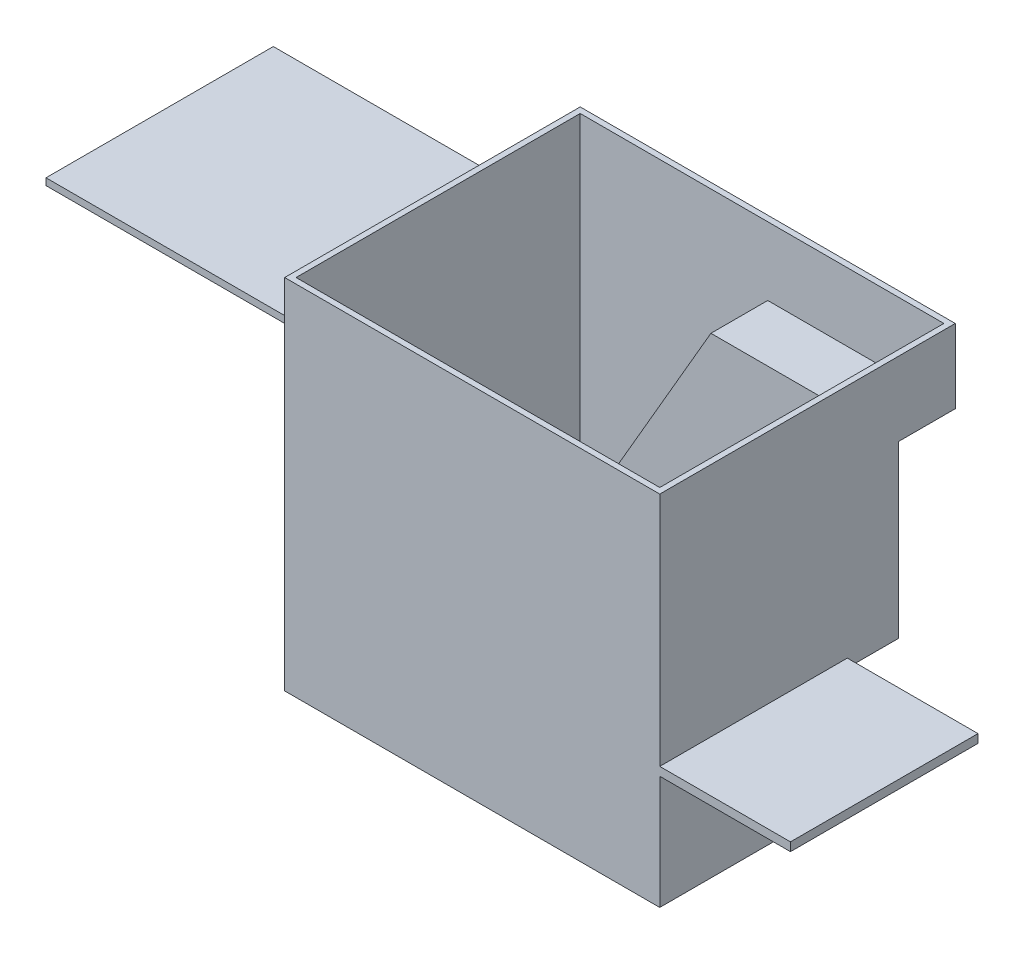
SolidWorks part; units mm, degrees
material "松木"
ref_plane "前视基准面" through (0, 0, 0) normal (0, 0, 1) x (1, 0, 0)
ref_plane "上视基准面" through (0, 0, 0) normal (0, 1, 0) x (1, 0, 0)
ref_plane "右视基准面" through (0, 0, 0) normal (1, 0, 0) x (0, 0, -1)
other "Configuration Table"
sketch "草图1" plane through (0, 0, 0) normal (0, 1, 0) x (1, 0, 0)
  line L0 (0, 300) -> (0, 510)
  line L1 (0, 0) -> (800, 0)
  line L2 (0, 0) -> (0, 300)
  line L3 (160, 320) -> (800, 320)
  line L4 (800, 0) -> (800, 320)
  line L5 (0, 510) -> (160, 510)
  line L6 (160, 510) -> (160, 320)
  dimension "D1" = 800
  dimension "D2" = 190
  dimension "D3" = 320
  dimension "D4" = 160
extrude "凸台-拉伸1" add sketch "草图1" along normal blind 10
sketch "草图2" plane through (0, 10, 0) normal (0, 1, 0) x (1, 0, 0)
  line L0 (160, 510) -> (0, 510) construction
  line L1 (0, 0) -> (10, 0)
  line L2 (0, 0) -> (0, 510)
  line L3 (0, 510) -> (10, 510)
  line L4 (10, 0) -> (10, 510)
  dimension "D1" = 10
extrude "凸台-拉伸2" add sketch "草图2" along normal blind 500
sketch "草图3" plane through (0, 0, -510) normal (0, 0, -1) x (-1, 0, 0)
  line L0 (-10, 510) -> (-10, 10)
  line L1 (-10, 10) -> (-160, 10)
  line L2 (-160, 10) -> (-450.0087, 510)
  line L3 (-450.0087, 510) -> (-10, 510)
extrude "凸台-拉伸3" add sketch "草图3" against normal blind 10
sketch "草图4" plane through (0, 0, -510) normal (0, 0, -1) x (-1, 0, 0)
  line L0 (-276.0035, 210) -> (-160, 10)
  line L1 (-160, 10) -> (-160, 0)
  line L2 (-160, 10) -> (-160, 0) construction
  line L3 (-160, 0) -> (-169.7622, 0)
  line L4 (-800, 0) -> (-160, 0) construction
  line L5 (-169.7622, 0) -> (-169.7622, 10)
  line L6 (-800, 10) -> (-160, 10) construction
  line L7 (-169.7622, 10) -> (-285.7657, 210)
  line L9 (-285.7657, 210) -> (-276.0035, 210)
  dimension "D1" = 200
extrude "凸台-拉伸4" add sketch "草图4" against normal up to surface (190 mm away) up to face at (480, 5, -320)
sketch "草图5" plane through (0, 10, 0) normal (0, 1, 0) x (1, 0, 0)
  line L1 (800, 320) -> (160, 320)
  line L2 (800, 320) -> (800, 310)
  line L3 (800, 310) -> (160, 310)
  line L4 (160, 320) -> (160, 310)
  dimension "D1" = 10
extrude "凸台-拉伸5" add sketch "草图5" along normal blind 200
sketch "草图6" plane through (0, 0, -320) normal (0, 0, -1) x (-1, 0, 0)
  line L0 (-160, 210) -> (-276.0035, 210)
  line L1 (-276.0035, 210) -> (-160, 10)
  line L2 (-160, 10) -> (-160, 210)
extrude "切除-拉伸1" cut sketch "草图6" against normal blind 20
sketch "草图7" plane through (0, 210, 0) normal (0, 1, 0) x (1, 0, 0)
  line L6 (276.0035, 310) -> (800, 310)
  line L7 (276.0035, 310) -> (276.0035, 410)
  line L8 (276.0035, 410) -> (800, 410)
  line L9 (800, 310) -> (800, 410)
  dimension "D1" = 100
extrude "凸台-拉伸7" add sketch "草图7" against normal blind 10
sketch "草图8" plane through (0, 0, -510) normal (0, 0, -1) x (-1, 0, 0)
  line L0 (-276.0035, 210) -> (-450.0087, 510)
  line L1 (-276.0035, 210) -> (-285.7657, 210)
  line L2 (-285.7657, 210) -> (-459.7709, 510)
  line L3 (-459.7709, 510) -> (-450.0087, 510)
extrude "凸台-拉伸8" add sketch "草图8" against normal up to surface (100 mm away) up to face at (541.4328, 205, -410)
sketch "草图9" plane through (0, 0, -410) normal (0, 0, 1) x (1, 0, 0)
  line L0 (276.0035, 210) -> (450.0087, 510)
  line L1 (450.0087, 510) -> (800, 510)
  line L2 (800, 510) -> (800, 210)
  line L3 (800, 210) -> (276.0035, 210)
extrude "凸台-拉伸9" add sketch "草图9" along normal blind 10
sketch "草图10" plane through (800, 0, 0) normal (1, 0, 0) x (0, 0, -1)
  line L0 (0, 0) -> (320, 0)
  line L1 (320, 0) -> (320, 200)
  line L2 (320, 200) -> (410, 200)
  line L3 (410, 200) -> (410, 510)
  line L4 (410, 510) -> (0, 510)
  line L5 (0, 510) -> (0, 0)
extrude "凸台-拉伸10" add sketch "草图10" along normal blind 10
sketch "草图11" plane through (0, 0, 0) normal (0, 0, 1) x (1, 0, 0)
  line L1 (0, 510) -> (810, 510)
  line L2 (0, 510) -> (0, 0)
  line L3 (0, 0) -> (810, 0)
  line L4 (810, 510) -> (810, 0)
extrude "凸台-拉伸11" add sketch "草图11" along normal blind 10
sketch "草图12" plane through (0, 0, 0) normal (-1, 0, 0) x (0, 0, 1)
  line L1 (-510, 510) -> (10, 510)
  line L2 (-510, 510) -> (-510, 0)
  line L3 (-510, 0) -> (10, 0)
  line L4 (10, 510) -> (10, 0)
extrude "切除-拉伸2" cut sketch "草图12" against normal blind 120
sketch "草图13" plane through (810, 0, 0) normal (1, 0, 0) x (0, 0, -1)
  line L1 (-10, 510) -> (510, 510)
  line L2 (-10, 510) -> (-10, 0)
  line L3 (-10, 0) -> (510, 0)
  line L4 (510, 510) -> (510, 0)
extrude "切除-拉伸3" cut sketch "草图13" against normal blind 50
sketch "草图14" plane through (760, 0, 0) normal (1, 0, 0) x (0, 0, -1)
  line L1 (-10, 510) -> (320, 510)
  line L2 (-10, 510) -> (-10, 0)
  line L3 (-10, 0) -> (320, 0)
  line L4 (320, 200) -> (320, 0)
  line L5 (320, 510) -> (410, 510)
  line L7 (320, 200) -> (410, 200)
  line L8 (410, 510) -> (410, 200)
extrude "凸台-拉伸12" add sketch "草图14" along normal blind 10
sketch "草图15" plane through (120, 0, 0) normal (-1, 0, 0) x (0, 0, 1)
  line L1 (-510, 510) -> (10, 510)
  line L2 (-510, 510) -> (-510, 0)
  line L3 (-510, 0) -> (10, 0)
  line L4 (10, 510) -> (10, 0)
extrude "凸台-拉伸13" add sketch "草图15" along normal blind 10
sketch "草图17" plane through (0, 0, -410) normal (0, 0, -1) x (-1, 0, 0)
  line L0 (-770, 510) -> (-459.7709, 510)
  line L1 (-459.7709, 510) -> (-453.9707, 500)
  line L2 (-459.7709, 510) -> (-169.7622, 10) construction
  line L3 (-453.9707, 500) -> (-770, 500)
  line L4 (-770, 200) -> (-770, 510) construction
  line L5 (-770, 500) -> (-770, 510)
  dimension "D1" = 10
extrude "凸台-拉伸15" add sketch "草图17" along normal up to surface (100 mm away) up to face at (203.8591, 206, -510)
sketch "草图18" plane through (0, 510, 0) normal (0, 1, 0) x (1, 0, 0)
  line L1 (110, 510) -> (770, 510)
  line L2 (110, 510) -> (110, -10)
  line L3 (110, -10) -> (770, -10)
  line L4 (770, 510) -> (770, -10)
  line L5 (120, 500) -> (760, 500)
  line L6 (120, 500) -> (120, 0)
  line L7 (120, 0) -> (760, 0)
  line L8 (760, 500) -> (760, 0)
extrude "凸台-拉伸16" add sketch "草图18" along normal blind 120
sketch "草图19" plane through (110, 0, 0) normal (-1, 0, 0) x (0, 0, 1)
  line L0 (-510, 0) -> (10, 0) construction
  line L1 (-450, 512) -> (-50, 512)
  line L2 (-450, 512) -> (-450, 500)
  line L3 (-450, 500) -> (-50, 500)
  line L4 (-50, 512) -> (-50, 500)
  line L5 (-510, 630) -> (10, 630) construction
  point P6 (-250, 512)
  point P9 (-250, 630)
  dimension "D1" = 12
  dimension "D2" = 500
  dimension "D3" = 0
  dimension "D4" = 400
extrude "凸台-拉伸17" add sketch "草图19" along normal blind 480
sketch "草图20" plane through (770, 0, 0) normal (1, 0, 0) x (0, 0, -1)
  line L0 (-10, 630) -> (-10, 0) construction
  line L1 (320, 200) -> (-10, 200)
  line L3 (320, 215) -> (-10, 215)
  line L4 (-10, 200) -> (-10, 215)
  line L5 (320, 200) -> (320, 215)
  dimension "D1" = 15
extrude "凸台-拉伸18" add sketch "草图20" along normal blind 230
